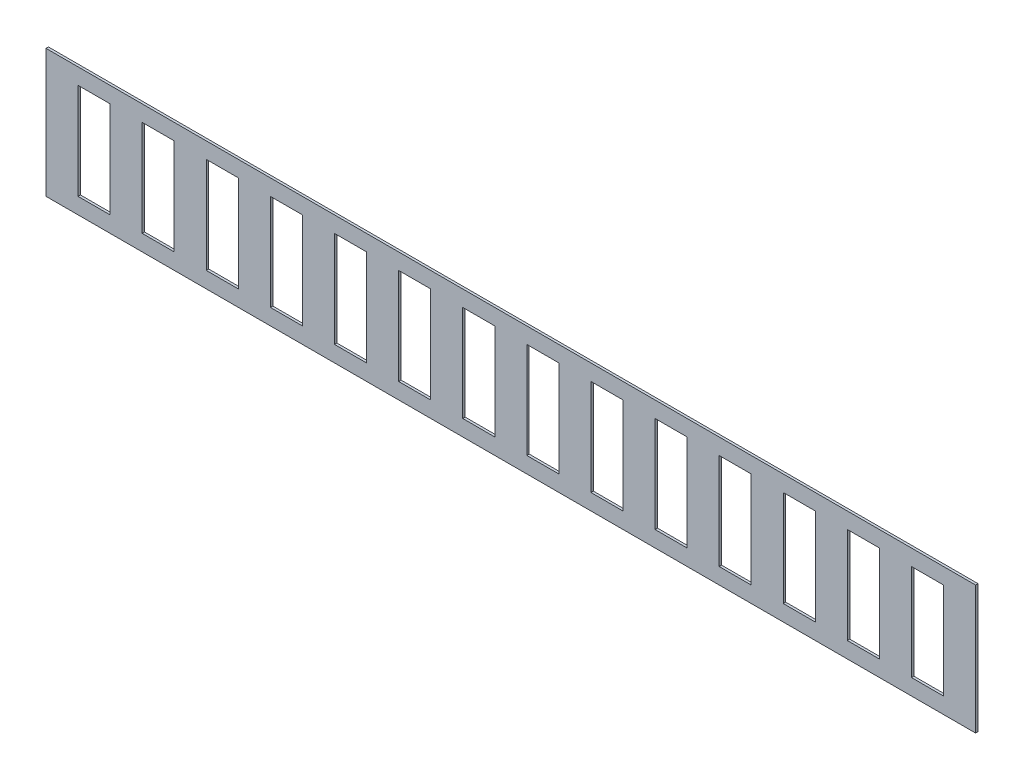
SolidWorks part; units mm, degrees
ref_plane "Front Plane" through (0, 0, 0) normal (0, 0, 1) x (1, 0, 0)
ref_plane "Top Plane" through (0, 0, 0) normal (0, 1, 0) x (1, 0, 0)
ref_plane "Right Plane" through (0, 0, 0) normal (1, 0, 0) x (0, 0, -1)
other "Configuration Table"
sketch "Sketch1" plane through (0, 0, 0) normal (0, 0, 1) x (1, 0, 0)
  line L1 (60, 30) -> (640, 30)
  line L2 (60, 30) -> (60, 110)
  line L3 (60, 110) -> (640, 110)
  line L4 (640, 30) -> (640, 110)
extrude "PACK_plint_izgara_paneli_1" add sketch "Sketch1" along normal blind 1.5 from offset 18.5 separate body
sketch "Sketch2" plane through (0, 0, 0) normal (0, 0, 1) x (1, 0, 0)
  line L1 (80, 40) -> (100, 40)
  line L2 (80, 40) -> (80, 100)
  line L3 (80, 100) -> (100, 100)
  line L4 (100, 40) -> (100, 100)
extrude "PACK_plint_izgara_paneli_2" cut sketch "Sketch2" along normal blind 4 from offset 17
sketch "Sketch3" plane through (0, 0, 0) normal (0, 0, 1) x (1, 0, 0)
  line L1 (120, 40) -> (140, 40)
  line L2 (120, 40) -> (120, 100)
  line L3 (120, 100) -> (140, 100)
  line L4 (140, 40) -> (140, 100)
extrude "PACK_plint_izgara_paneli_3" cut sketch "Sketch3" along normal blind 4 from offset 17
sketch "Sketch4" plane through (0, 0, 0) normal (0, 0, 1) x (1, 0, 0)
  line L1 (160, 40) -> (180, 40)
  line L2 (160, 40) -> (160, 100)
  line L3 (160, 100) -> (180, 100)
  line L4 (180, 40) -> (180, 100)
extrude "PACK_plint_izgara_paneli_4" cut sketch "Sketch4" along normal blind 4 from offset 17
sketch "Sketch5" plane through (0, 0, 0) normal (0, 0, 1) x (1, 0, 0)
  line L1 (200, 40) -> (220, 40)
  line L2 (200, 40) -> (200, 100)
  line L3 (200, 100) -> (220, 100)
  line L4 (220, 40) -> (220, 100)
extrude "PACK_plint_izgara_paneli_5" cut sketch "Sketch5" along normal blind 4 from offset 17
sketch "Sketch6" plane through (0, 0, 0) normal (0, 0, 1) x (1, 0, 0)
  line L1 (240, 40) -> (260, 40)
  line L2 (240, 40) -> (240, 100)
  line L3 (240, 100) -> (260, 100)
  line L4 (260, 40) -> (260, 100)
extrude "PACK_plint_izgara_paneli_6" cut sketch "Sketch6" along normal blind 4 from offset 17
sketch "Sketch7" plane through (0, 0, 0) normal (0, 0, 1) x (1, 0, 0)
  line L1 (280, 40) -> (300, 40)
  line L2 (280, 40) -> (280, 100)
  line L3 (280, 100) -> (300, 100)
  line L4 (300, 40) -> (300, 100)
extrude "PACK_plint_izgara_paneli_7" cut sketch "Sketch7" along normal blind 4 from offset 17
sketch "Sketch8" plane through (0, 0, 0) normal (0, 0, 1) x (1, 0, 0)
  line L1 (320, 40) -> (340, 40)
  line L2 (320, 40) -> (320, 100)
  line L3 (320, 100) -> (340, 100)
  line L4 (340, 40) -> (340, 100)
extrude "PACK_plint_izgara_paneli_8" cut sketch "Sketch8" along normal blind 4 from offset 17
sketch "Sketch9" plane through (0, 0, 0) normal (0, 0, 1) x (1, 0, 0)
  line L1 (360, 40) -> (380, 40)
  line L2 (360, 40) -> (360, 100)
  line L3 (360, 100) -> (380, 100)
  line L4 (380, 40) -> (380, 100)
extrude "PACK_plint_izgara_paneli_9" cut sketch "Sketch9" along normal blind 4 from offset 17
sketch "Sketch10" plane through (0, 0, 0) normal (0, 0, 1) x (1, 0, 0)
  line L1 (400, 40) -> (420, 40)
  line L2 (400, 40) -> (400, 100)
  line L3 (400, 100) -> (420, 100)
  line L4 (420, 40) -> (420, 100)
extrude "PACK_plint_izgara_paneli_10" cut sketch "Sketch10" along normal blind 4 from offset 17
sketch "Sketch11" plane through (0, 0, 0) normal (0, 0, 1) x (1, 0, 0)
  line L1 (440, 40) -> (460, 40)
  line L2 (440, 40) -> (440, 100)
  line L3 (440, 100) -> (460, 100)
  line L4 (460, 40) -> (460, 100)
extrude "PACK_plint_izgara_paneli_11" cut sketch "Sketch11" along normal blind 4 from offset 17
sketch "Sketch12" plane through (0, 0, 0) normal (0, 0, 1) x (1, 0, 0)
  line L1 (480, 40) -> (500, 40)
  line L2 (480, 40) -> (480, 100)
  line L3 (480, 100) -> (500, 100)
  line L4 (500, 40) -> (500, 100)
extrude "PACK_plint_izgara_paneli_12" cut sketch "Sketch12" along normal blind 4 from offset 17
sketch "Sketch13" plane through (0, 0, 0) normal (0, 0, 1) x (1, 0, 0)
  line L1 (520, 40) -> (540, 40)
  line L2 (520, 40) -> (520, 100)
  line L3 (520, 100) -> (540, 100)
  line L4 (540, 40) -> (540, 100)
extrude "PACK_plint_izgara_paneli_13" cut sketch "Sketch13" along normal blind 4 from offset 17
sketch "Sketch14" plane through (0, 0, 0) normal (0, 0, 1) x (1, 0, 0)
  line L1 (560, 40) -> (580, 40)
  line L2 (560, 40) -> (560, 100)
  line L3 (560, 100) -> (580, 100)
  line L4 (580, 40) -> (580, 100)
extrude "PACK_plint_izgara_paneli_14" cut sketch "Sketch14" along normal blind 4 from offset 17
sketch "Sketch15" plane through (0, 0, 0) normal (0, 0, 1) x (1, 0, 0)
  line L1 (600, 40) -> (620, 40)
  line L2 (600, 40) -> (600, 100)
  line L3 (600, 100) -> (620, 100)
  line L4 (620, 40) -> (620, 100)
extrude "PACK_plint_izgara_paneli_15" cut sketch "Sketch15" along normal blind 4 from offset 17
